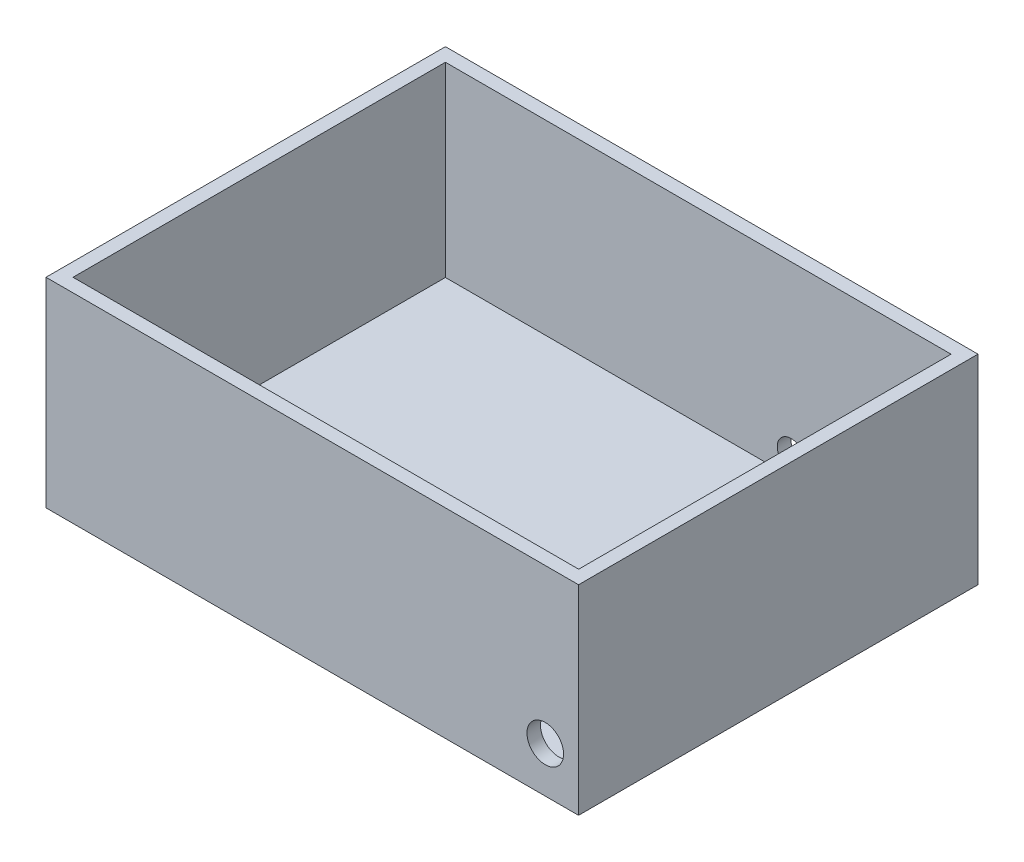
SolidWorks part; units mm, degrees
ref_plane "Front Plane" through (0, 0, 0) normal (0, 0, 1) x (1, 0, 0)
ref_plane "Top Plane" through (0, 0, 0) normal (0, 1, 0) x (1, 0, 0)
ref_plane "Right Plane" through (0, 0, 0) normal (1, 0, 0) x (0, 0, -1)
sketch "Sketch1" plane through (0, 0, 0) normal (0, 1, 0) x (1, 0, 0)
  line L1 (-106.5937, 87.7685) -> (96.6063, 87.7685)
  line L2 (-106.5937, 87.7685) -> (-106.5937, -64.6315)
  line L3 (-106.5937, -64.6315) -> (96.6063, -64.6315)
  line L4 (96.6063, 87.7685) -> (96.6063, -64.6315)
  line L6 (-106.5937, 87.7685) -> (-101.4407, 87.7685)
  dimension "D1" = 203.2
  dimension "D2" = 152.4
sketch "Sketch4" plane through (0, 0, 0) normal (0, 1, 0) x (1, 0, 0)
  line L1 (-106.5937, 87.7685) -> (96.6063, 87.7685)
  line L2 (-106.5937, 87.7685) -> (-106.5937, -64.6315)
  line L3 (-106.5937, -64.6315) -> (96.6063, -64.6315)
  line L4 (96.6063, 87.7685) -> (96.6063, -64.6315)
extrude "Boss-Extrude3" add sketch "Sketch4" along normal blind 76.2
sketch "Sketch11" plane through (0, 0, 0) normal (0, -1, 0) x (1, 0, 0)
  text T0 "<b>The Only WGT</b>\r\n<b>Team #25</b>" font "Century Gothic" height 3.5
sketch "Sketch13" plane through (0, 76.2, 0) normal (0, 1, 0) x (1, 0, 0)
  line L0 (-101.4407, 82.6126) -> (-101.4407, -59.4756)
  line L2 (-101.4407, 82.6126) -> (91.486, 82.6126)
  line L5 (-101.4407, -59.4756) -> (91.486, -59.4756)
  line L8 (91.486, 82.6126) -> (91.486, -59.4756)
extrude "Cut-Extrude9" cut sketch "Sketch13" against normal blind 71.12
sketch "Sketch18" plane through (0, 0, -82.6126) normal (0, 0, 1) x (1, 0, 0)
  line L0 (30.4914, 12.505) -> (83.8314, 12.505)
  circle A6 centre (83.8314, 12.505) radius 5.334
  circle A8 centre (30.4914, 12.505) radius 5.334
  point P2 (28.8141, 14.5781)
  point P3 (0, 0)
  point P4 (0, 0)
  point P5 (83.8314, 12.505)
  point P6 (0, 0)
  point P9 (0, 0)
  dimension "D1" = 10.668
  dimension "D2" = 10.668
  dimension "D3" = 53.34
sketch "Sketch20" plane through (0, 0, 59.4756) normal (0, 0, -1) x (-1, 0, 0)
  circle A0 centre (-83.8988, 17.3591) radius 6.35
extrude "Cut-Extrude15" cut sketch "Sketch20" along normal blind 6.604 and the other way blind 12.7
extrude "Cut-Extrude17" cut sketch "Sketch18" against normal blind 12.7 contours A8 | A6
sketch "Sketch23" plane through (0, 0, 64.6315) normal (0, 0, 1) x (1, 0, 0)
  circle A0 centre (83.8988, 17.3591) radius 6.985
  point P3 (83.8988, 17.3591)
  point P4 (83.8988, 17.3591)
  dimension "D1" = 13.97
extrude "Cut-Extrude20" cut sketch "Sketch23" along normal blind 12.446 and the other way blind 10.922
sketch "Sketch24" plane through (0, 0, 0) normal (0, -1, 0) x (1, 0, 0)
  text T0 "<b>THE ONLY WGT</b>\r\nTEAM 25\r\nVERSION 1"
extrude "Cut-Extrude21" cut sketch "Sketch24" against normal blind 3.81
